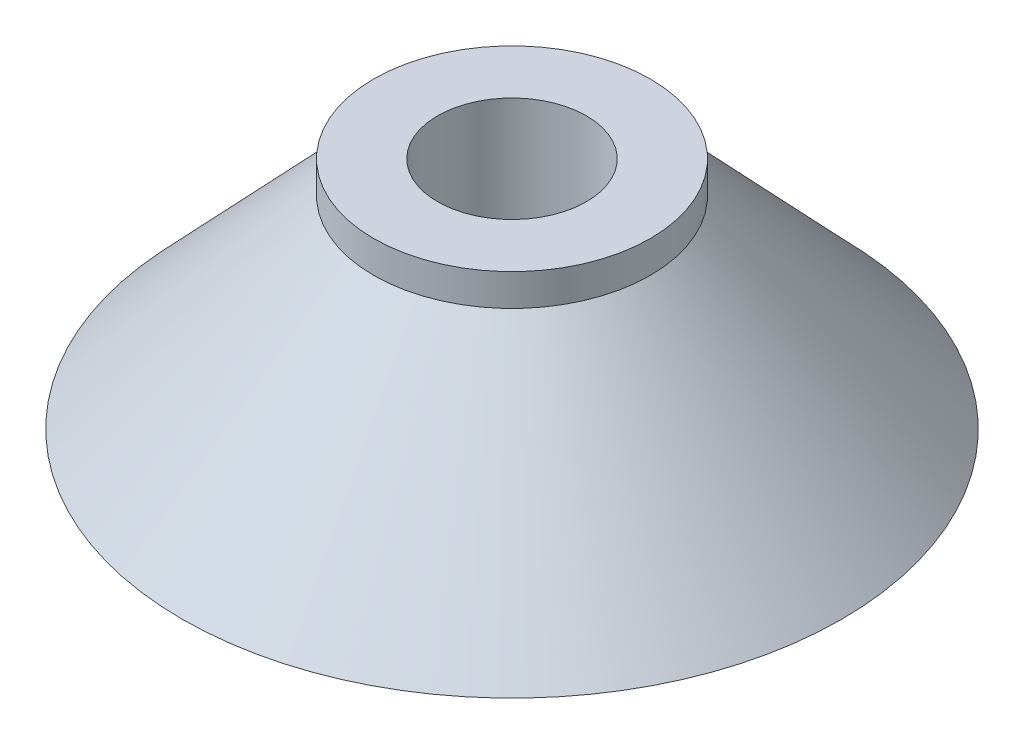
SolidWorks part; units mm, degrees
ref_plane "Спереди" through (0, 0, 0) normal (0, 0, 1) x (1, 0, 0)
ref_plane "Сверху" through (0, 0, 0) normal (0, 1, 0) x (1, 0, 0)
ref_plane "Справа" through (0, 0, 0) normal (1, 0, 0) x (0, 0, -1)
sketch "Эскиз1" plane through (0, 0, 0) normal (0, 0, 1) x (1, 0, 0)
  line L0 (0, 0) -> (0, 9.207) construction
  line L1 (3.25, 4.75) -> (7.75, 0)
  line L2 (1.75, 5.5) -> (3.25, 5.5)
  line L3 (1.75, 5.5) -> (1.75, 0)
  line L4 (1.75, 0) -> (3.25, 0)
  line L5 (3.25, 5.5) -> (3.25, 0)
  line L6 (3.25, 0) -> (7.75, 0)
  dimension "D1" = 5.5
  dimension "D2" = 1.5
  dimension "D3" = 1.75
  dimension "D4" = 0.75
  dimension "D5" = 4.5
revolve "Повернуть1" add sketch "Эскиз1" angle 360 about L0
